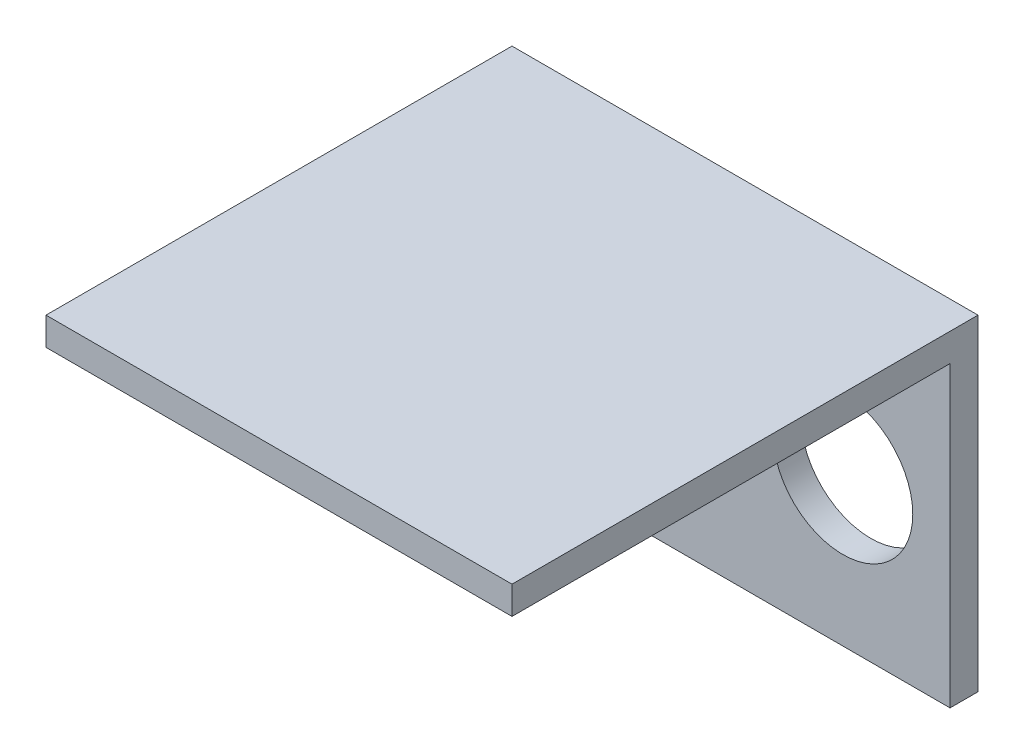
SolidWorks part; units mm, degrees
ref_plane "Plano frontal" through (0, 0, 0) normal (0, 0, 1) x (1, 0, 0)
ref_plane "Plano superior" through (0, 0, 0) normal (0, 1, 0) x (1, 0, 0)
ref_plane "Plano direito" through (0, 0, 0) normal (1, 0, 0) x (0, 0, -1)
sketch "Esboço2" plane through (0, 0, 0) normal (0, 1, 0) x (1, 0, 0)
  line L1 (-37.8761, -39.1833) -> (12.1239, -39.1833)
  line L2 (-37.8761, -39.1833) -> (-37.8761, 10.8167)
  line L3 (-37.8761, 10.8167) -> (12.1239, 10.8167)
  line L4 (12.1239, -39.1833) -> (12.1239, 10.8167)
  dimension "D1" = 50
  dimension "35" = 50
extrude "Ressalto-extrusão1" add sketch "Esboço2" along normal blind 3
sketch "Esboço4" plane through (0, 0, 0) normal (0, -1, 0) x (-1, 0, 0)
  line L0 (37.8761, 10.8167) -> (37.8761, -39.1833) construction
  line L1 (-12.1239, 10.8167) -> (37.8761, 10.8167)
  line L2 (-12.1239, 10.8167) -> (-12.1239, 7.8167)
  line L3 (-12.1239, 7.8167) -> (37.8761, 7.8167)
  line L4 (37.8761, 10.8167) -> (37.8761, 7.8167)
  dimension "D1" = 3
extrude "Ressalto-extrusão2" add sketch "Esboço4" along normal blind 32
sketch "Esboço6" plane through (0, 0, -7.8167) normal (0, 0, 1) x (1, 0, 0)
  line L0 (12.1239, -32) -> (12.1239, 0) construction
  line L4 (12.1239, -32) -> (-37.8761, -32) construction
  circle A0 centre (-26.3761, -16) radius 7.5
  circle A1 centre (0.6239, -16) radius 7.5
  dimension "D1" = 15
  dimension "D2" = 15
  dimension "D3" = 27
  dimension "D4" = 11.5
  dimension "D5" = 16
  dimension "D6" = 16
extrude "Corte-extrusão1" cut sketch "Esboço6" against normal through all
